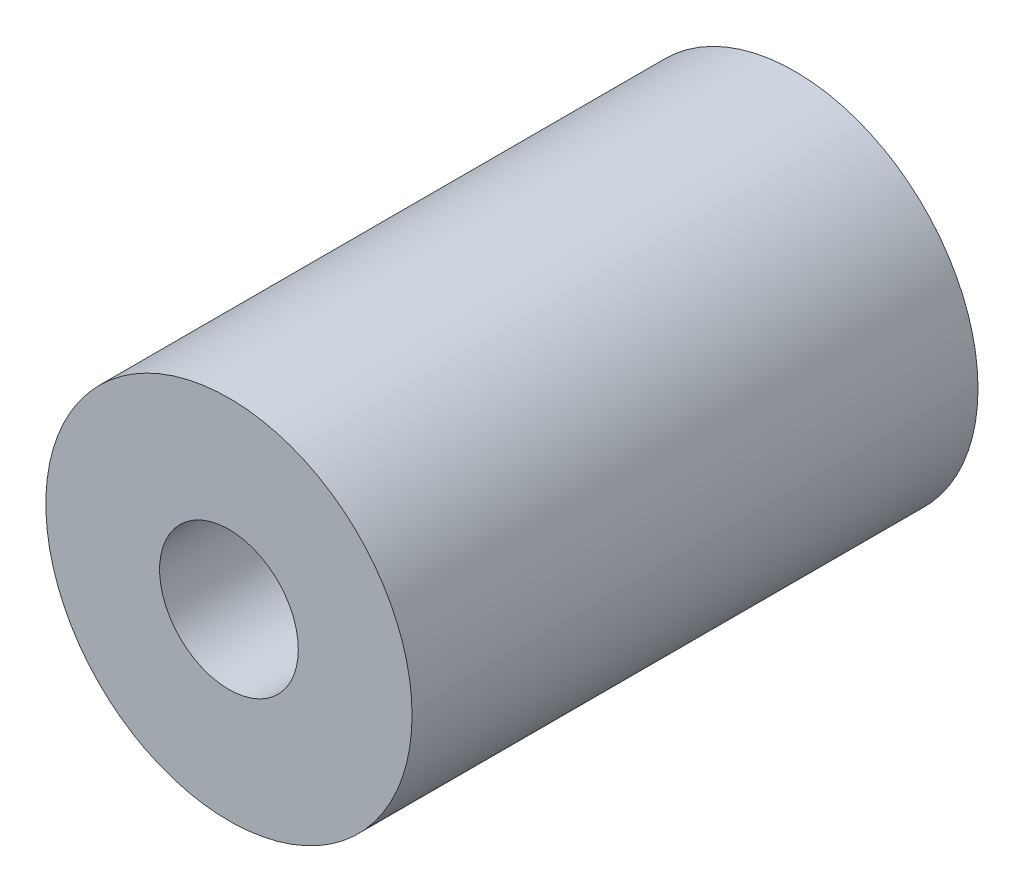
SolidWorks part; units mm, degrees
ref_plane "Front Plane" through (0, 0, 0) normal (0, 0, 1) x (1, 0, 0)
ref_plane "Top Plane" through (0, 0, 0) normal (0, 1, 0) x (1, 0, 0)
ref_plane "Right Plane" through (0, 0, 0) normal (1, 0, 0) x (0, 0, -1)
sketch "Sketch1" plane through (0, 0, 0) normal (0, 0, 1) x (1, 0, 0)
  circle A0 centre (0, 0) radius 33
  circle A1 centre (0, 0) radius 12.5
  dimension "D1" = 66
  dimension "D2" = 25
extrude "Boss-Extrude1" add sketch "Sketch1" along normal blind 102
